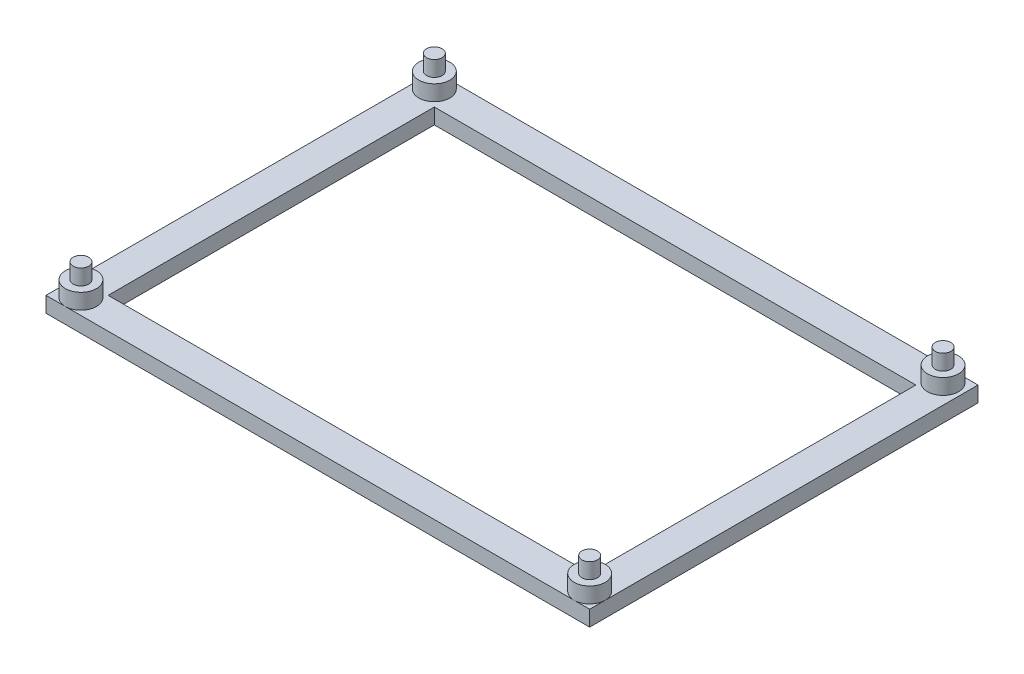
SolidWorks part; units mm, degrees
ref_plane "Front Plane" through (0, 0, 0) normal (0, 0, 1) x (1, 0, 0)
ref_plane "Top Plane" through (0, 0, 0) normal (0, 1, 0) x (1, 0, 0)
ref_plane "Right Plane" through (0, 0, 0) normal (1, 0, 0) x (0, 0, -1)
sketch "Sketch1" plane through (0, 0, 0) normal (0, 1, 0) x (1, 0, 0)
  line L1 (-35, -25) -> (35, -25)
  line L2 (-35, -25) -> (-35, 25)
  line L3 (-35, 25) -> (35, 25)
  line L4 (35, -25) -> (35, 25)
  line L5 (-35, -25) -> (35, 25) construction
  line L6 (-35, 25) -> (35, -25) construction
  point P0 (0, 0)
  dimension "D1" = 70
  dimension "D2" = 50
extrude "Boss-Extrude1" add sketch "Sketch1" along normal blind 2
sketch "Sketch2" plane through (0, 2, 0) normal (0, 1, 0) x (1, 0, 0)
  line L0 (-35, -25) -> (35, -25) construction
  line L5 (35, 25) -> (-35, 25) construction
  line L6 (35, -25) -> (35, 25) construction
  line L7 (-35, 25) -> (-35, -25) construction
  circle A0 centre (-33, 23) radius 1
  circle A1 centre (32.5, 23) radius 1
  circle A2 centre (33, -23) radius 1
  circle A3 centre (-32.5, -23) radius 1
  point P0 (0, 0)
  point P18 (-62.2881, 41.9499)
  dimension "D1" = 2
  dimension "D2" = 2
  dimension "D3" = 2
  dimension "D4" = 2
  dimension "D5" = 2
  dimension "D6" = 2
  dimension "D7" = 2
  dimension "D8" = 2
  dimension "D9" = 2
  dimension "D10" = 2.5
extrude "Boss-Extrude2" add sketch "Sketch2" along normal blind 4 contours A3 | A0 | A1 | A2
sketch "Sketch3" plane through (0, 2, 0) normal (0, 1, 0) x (1, 0, 0)
  circle A0 centre (-33, 23) radius 2
  circle A1 centre (32.5, 23) radius 2
  circle A2 centre (33, -23) radius 2
  circle A3 centre (-32.5, -23) radius 2
  circle A4 centre (-33, 23) radius 1 construction
  circle A5 centre (32.5, 23) radius 1 construction
  circle A6 centre (33, -23) radius 1 construction
  circle A7 centre (-32.5, -23) radius 1 construction
  dimension "D1" = 1
  dimension "D2" = 1
  dimension "D3" = 1
  dimension "D4" = 1
extrude "Boss-Extrude3" add sketch "Sketch3" along normal blind 2
sketch "Sketch4" plane through (0, 2, 0) normal (0, 1, 0) x (1, 0, 0)
  line L1 (31, -21) -> (-31, -21)
  line L2 (31, -21) -> (31, 21)
  line L3 (31, 21) -> (-31, 21)
  line L4 (-31, -21) -> (-31, 21)
  line L5 (31, -21) -> (-31, 21) construction
  line L6 (31, 21) -> (-31, -21) construction
  point P0 (0, 0)
  dimension "D1" = 62
  dimension "D2" = 42
extrude "Cut-Extrude1" cut sketch "Sketch4" against normal blind 2
